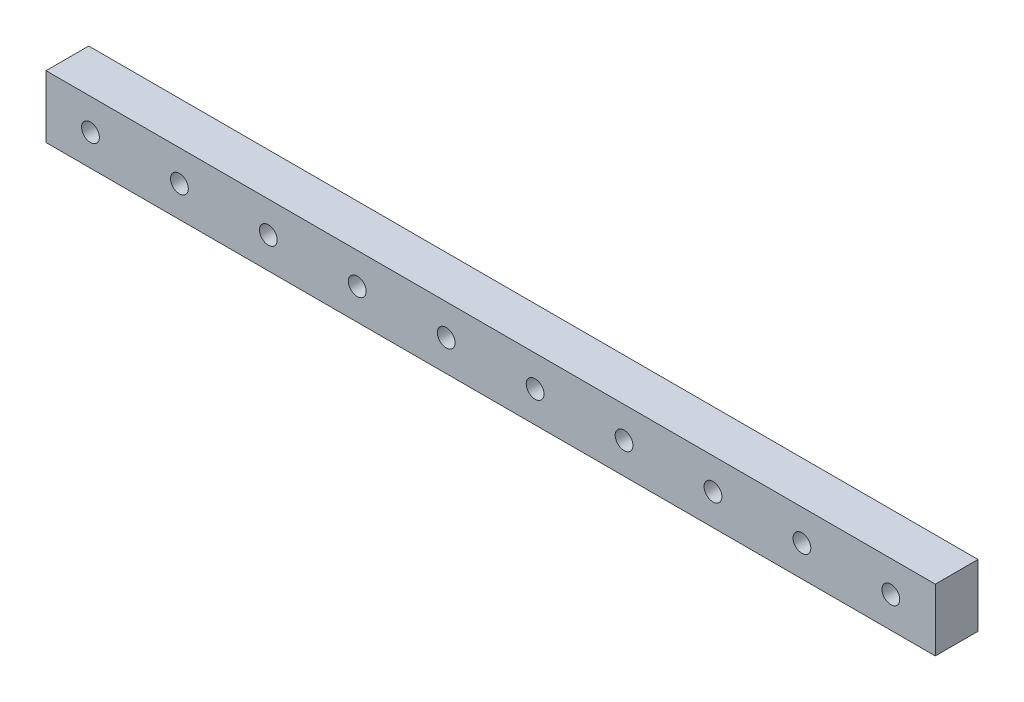
SolidWorks part; units mm, degrees
material "AISI 1015 钢，冷拔 (SS)"
ref_plane "前视基准面" through (0, 0, 0) normal (0, 0, 1) x (1, 0, 0)
ref_plane "上视基准面" through (0, 0, 0) normal (0, 1, 0) x (1, 0, 0)
ref_plane "右视基准面" through (0, 0, 0) normal (1, 0, 0) x (0, 0, -1)
sketch "草图1" plane through (0, 0, 0) normal (0, 0, 1) x (1, 0, 0)
  line L1 (0, 0) -> (100, 0)
  line L2 (0, 0) -> (0, 7)
  line L3 (0, 7) -> (100, 7)
  line L4 (100, 0) -> (100, 7)
  dimension "D1" = 100
  dimension "D2" = 7
extrude "凸台-拉伸1" add sketch "草图1" along normal blind 4.8
sketch "草图2" plane through (0, 0, 4.8) normal (0, 0, 1) x (1, 0, 0)
  line L0 (0, 3.5) -> (100, 3.5)
  line L1 (0, 7) -> (0, 0) construction
  line L2 (100, 0) -> (100, 7) construction
  circle A0 centre (5, 3.5) radius 1
  circle A1 centre (15, 3.5) radius 1
  circle A2 centre (25, 3.5) radius 1
  circle A3 centre (35, 3.5) radius 1
  circle A4 centre (45, 3.5) radius 1
  circle A5 centre (55, 3.5) radius 1
  circle A6 centre (65, 3.5) radius 1
  circle A7 centre (75, 3.5) radius 1
  circle A8 centre (85, 3.5) radius 1
  circle A9 centre (95, 3.5) radius 1
  dimension "D1" = 2
  dimension "D2" = 5
  dimension "D4" = 10
  dimension "D3" = 10
extrude "切除-拉伸1" cut sketch "草图2" against normal blind 4.8 contours L0 A0 | L0 A0 | L0 A1 | L0 A1 | L0 A2 | L0 A2 | L0 A3 | L0 A3 | L0 A4 | L0 A4 | L0 A5 | L0 A5 | L0 A7 | L0 A7 | L0 A8 | L0 A8 | L0 A9 | L0 A9 | A6
